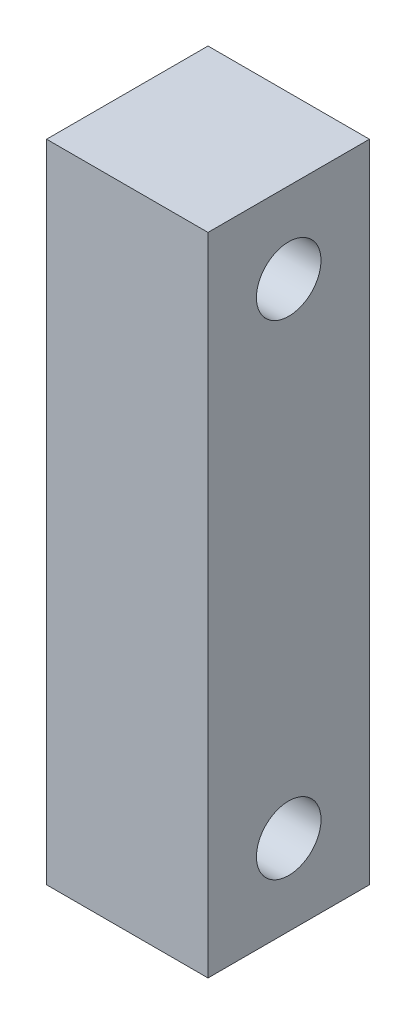
SolidWorks part; units mm, degrees
ref_plane "Front Plane" through (0, 0, 0) normal (0, 0, 1) x (1, 0, 0)
ref_plane "Top Plane" through (0, 0, 0) normal (0, 1, 0) x (1, 0, 0)
ref_plane "Right Plane" through (0, 0, 0) normal (1, 0, 0) x (0, 0, -1)
sketch "Sketch1" plane through (0, 0, 0) normal (0, 0, 1) x (1, 0, 0)
  line L0 (0, 0) -> (10, 0)
  line L2 (0, 0) -> (0, 40)
  line L3 (0, 40) -> (10, 40)
  line L4 (10, 0) -> (10, 40)
  dimension "D3" = 10
  dimension "D4" = 40
extrude "Boss-Extrude1" add sketch "Sketch1" along normal blind 10
sketch "Sketch3" plane through (0, 0, 0) normal (-1, 0, 0) x (0, 0, 1)
  line L0 (10, 40) -> (0, 40) construction
  line L1 (0, 40) -> (0, 0) construction
  line L2 (0, 20) -> (10, 20) construction
  line L3 (0, 40) -> (0, 0) construction
  line L4 (10, 40) -> (10, 0) construction
  circle A0 centre (5, 35) radius 2
  circle A1 centre (5, 5) radius 2
  dimension "D3" = 4
  dimension "D1" = 5
  dimension "D2" = 5
extrude "Cut-Extrude2" cut sketch "Sketch3" against normal through all
